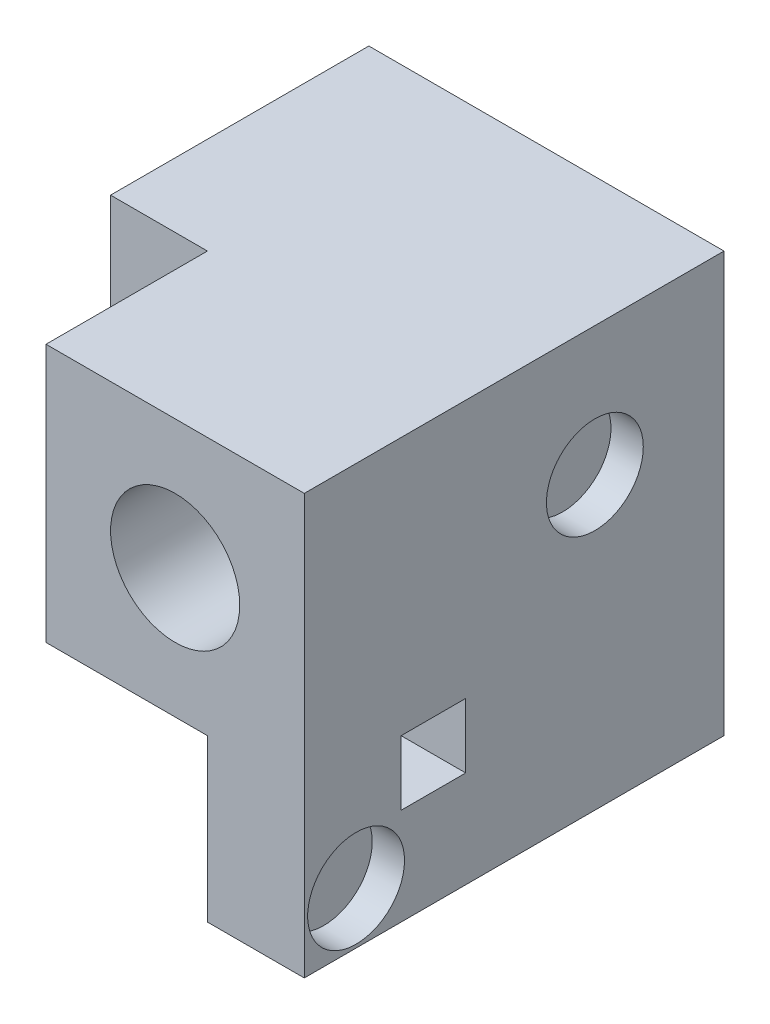
SolidWorks part; units mm, degrees
ref_plane "Plan de face" through (0, 0, 0) normal (0, 0, 1) x (1, 0, 0)
ref_plane "Plan de dessus" through (0, 0, 0) normal (0, 1, 0) x (1, 0, 0)
ref_plane "Plan de droite" through (0, 0, 0) normal (1, 0, 0) x (0, 0, -1)
sketch "Esquisse2" plane through (0, 0, 0) normal (0, 1, 0) x (1, 0, 0)
  line L1 (-40, 40) -> (40, 40)
  line L2 (-40, 40) -> (-40, -40)
  line L3 (-40, -40) -> (40, -40)
  line L4 (40, 40) -> (40, -40)
  line L5 (-40, 40) -> (40, -40) construction
  line L6 (-40, -40) -> (40, 40) construction
  point P0 (0, 0)
  dimension "D1" = 80
  dimension "D2" = 80
extrude "Boss.-Extru.1" add sketch "Esquisse2" along normal blind 80
sketch "Esquisse5" plane through (-40, 0, 0) normal (-1, 0, 0) x (0, 0, 1)
  line L1 (-40, 80) -> (40, 80)
  line L2 (-40, 80) -> (-40, 0)
  line L3 (-40, 0) -> (40, 0)
  line L4 (40, 80) -> (40, 0)
extrude "Boss.-Extru.2" add sketch "Esquisse5" along normal blind 30
sketch "Esquisse6" plane through (0, 0, 40) normal (0, 0, 1) x (1, 0, 0)
  line L0 (40, 40) -> (-40, 40) construction
  line L1 (40, 80) -> (40, 0) construction
  line L2 (-70, 0) -> (40, 0) construction
  line L3 (40, 80) -> (-40, 80)
  line L4 (40, 80) -> (40, 0)
  line L5 (40, 0) -> (-40, 0)
  line L6 (-40, 80) -> (-40, 0)
  dimension "D1" = 80
extrude "Boss.-Extru.3" add sketch "Esquisse6" along normal blind 50
sketch "Esquisse7" plane through (0, 0, 0) normal (0, -1, 0) x (1, 0, 0)
  line L1 (-40, 40) -> (40, 40)
  line L2 (-40, 40) -> (-40, -40)
  line L3 (-40, -40) -> (40, -40)
  line L4 (40, 40) -> (40, -40)
extrude "Boss.-Extru.4" add sketch "Esquisse7" along normal blind 50
sketch "Esquisse8" plane through (-70, 0, 0) normal (-1, 0, 0) x (0, 0, 1)
  line L0 (0, 0) -> (0, 80) construction
  line L1 (-40, 0) -> (40, 0) construction
  line L2 (40, 80) -> (-40, 80) construction
  circle A0 centre (0, 40) radius 20
  dimension "D1" = 40
extrude "Enlèv. mat.-Extru.1" cut sketch "Esquisse8" against normal blind 45
sketch "Esquisse9" plane through (0, 0, 90) normal (0, 0, 1) x (1, 0, 0)
  line L0 (0, 0) -> (0, 80) construction
  line L1 (-40, 0) -> (40, 0) construction
  line L2 (40, 80) -> (-40, 80) construction
  circle A0 centre (0, 40) radius 20
  dimension "D1" = 40
extrude "Enlèv. mat.-Extru.2" cut sketch "Esquisse9" against normal blind 65
sketch "Esquisse10" plane through (0, -50, 0) normal (0, -1, 0) x (1, 0, 0)
  line L0 (40, 0) -> (-40, 0) construction
  line L1 (40, -40) -> (40, 40) construction
  line L2 (-40, 40) -> (-40, -40) construction
  circle A0 centre (0, 0) radius 20
  dimension "D1" = 40
extrude "Enlèv. mat.-Extru.3" cut sketch "Esquisse10" against normal blind 65
ref_plane "Plan1" through (50, 0, 0) normal (1, 0, 0) x (0, 0, -1)
sketch "Esquisse16" plane through (0, 0, 0) normal (0, -1, 0) x (1, 0, 0)
  line L1 (40, 90) -> (10, 90)
  line L2 (40, 90) -> (40, 60)
  line L3 (40, 60) -> (10, 60)
  line L4 (10, 90) -> (10, 60)
  dimension "D1" = 30
  dimension "D2" = 30
extrude "Boss.-Extru.9" add sketch "Esquisse16" along normal blind 50
sketch "Esquisse17" plane through (0, 0, 40) normal (0, 0, 1) x (1, 0, 0)
  line L1 (40, -50) -> (10, -50)
  line L2 (40, -50) -> (40, -20)
  line L3 (40, -20) -> (10, -20)
  line L4 (10, -50) -> (10, -20)
  dimension "D1" = 30
  dimension "D2" = 30
extrude "Boss.-Extru.10" add sketch "Esquisse17" along normal blind 50
sketch "Esquisse19" plane through (40, 0, 0) normal (1, 0, 0) x (0, 0, -1)
  line L0 (40, 80) -> (-90, -50) construction
  line L1 (-40, 0) -> (40, 0) construction
  line L2 (40, 80) -> (40, -50) construction
  line L3 (40, 0) -> (-40, 80) construction
  circle A1 centre (-73.9564, -33.9564) radius 15
  circle A2 centre (0, 40) radius 15
  dimension "D1" = 30
  dimension "D2" = 30
extrude "Enlèv. mat.-Extru.4" cut sketch "Esquisse19" against normal blind 10
equation "\"40u\"=50.2739"
